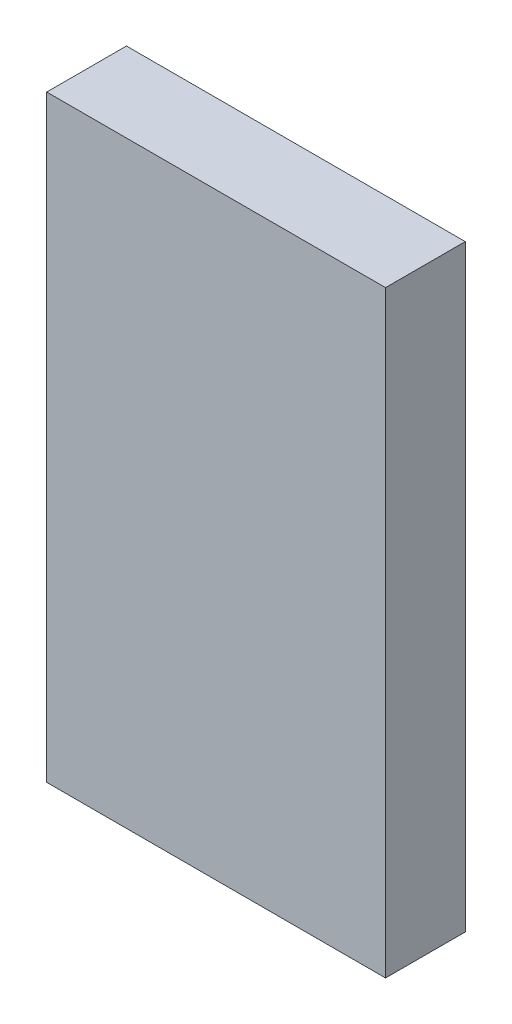
SolidWorks part; units mm, degrees
ref_plane "Front Plane" through (0, 0, 0) normal (0, 0, 1) x (1, 0, 0)
ref_plane "Top Plane" through (0, 0, 0) normal (0, 1, 0) x (1, 0, 0)
ref_plane "Right Plane" through (0, 0, 0) normal (1, 0, 0) x (0, 0, -1)
sketch "Sketch1" plane through (0, 0, 0) normal (0, 0, 1) x (1, 0, 0)
  line L1 (21.25, -37.5) -> (-21.25, -37.5)
  line L2 (21.25, -37.5) -> (21.25, 37.5)
  line L3 (21.25, 37.5) -> (-21.25, 37.5)
  line L4 (-21.25, -37.5) -> (-21.25, 37.5)
  line L5 (21.25, -37.5) -> (-21.25, 37.5) construction
  line L6 (21.25, 37.5) -> (-21.25, -37.5) construction
  point P0 (0, 0)
  dimension "D1" = 75
  dimension "D2" = 42.5
extrude "Boss-Extrude1" add sketch "Sketch1" along normal blind 10
